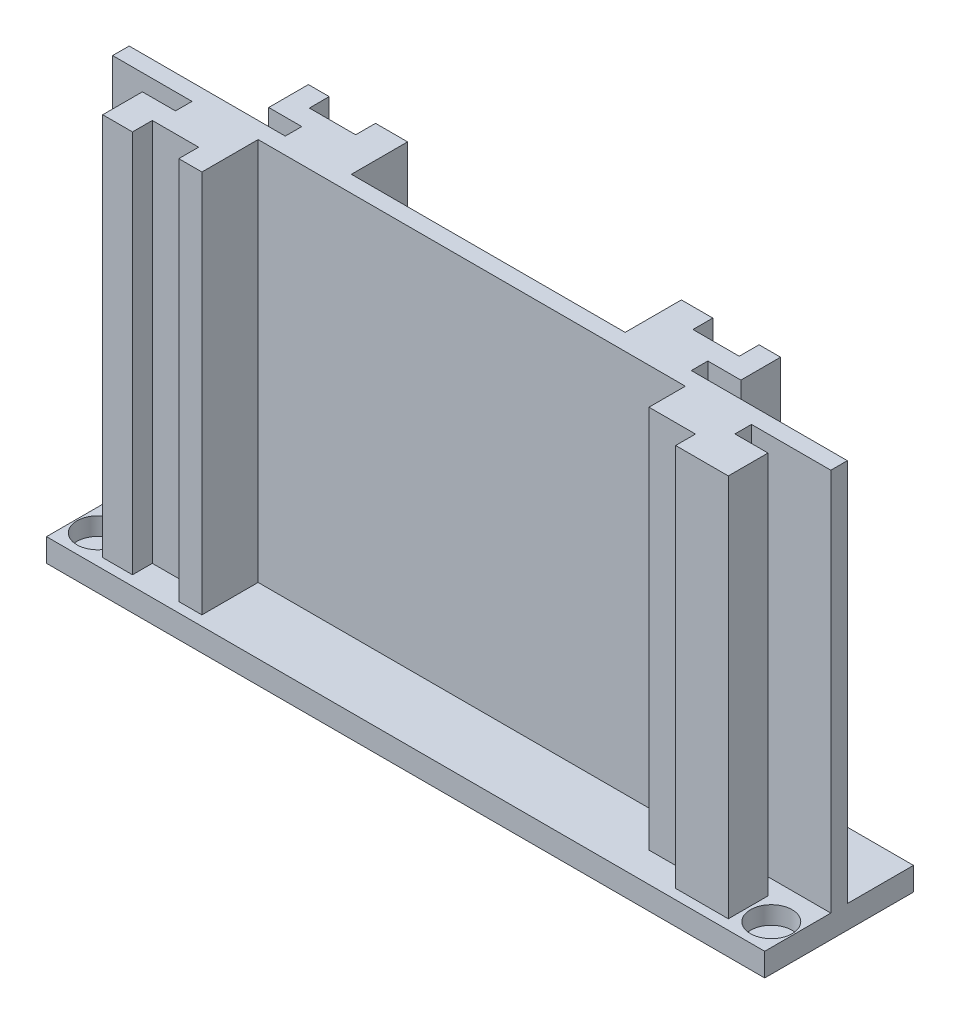
SolidWorks part; units mm, degrees
ref_plane "Front Plane" through (0, 0, 0) normal (0, 0, 1) x (1, 0, 0)
ref_plane "Top Plane" through (0, 0, 0) normal (0, 1, 0) x (1, 0, 0)
ref_plane "Right Plane" through (0, 0, 0) normal (1, 0, 0) x (0, 0, -1)
sketch "Sketch1" plane through (0, 0, 0) normal (0, 0, 1) x (1, 0, 0)
  line L1 (-54.3, -29) -> (54.3, -29)
  line L2 (-54.3, -29) -> (-54.3, 29)
  line L3 (-54.3, 29) -> (54.3, 29)
  line L4 (54.3, -29) -> (54.3, 29)
  line L5 (-54.3, -29) -> (54.3, 29) construction
  line L6 (-54.3, 29) -> (54.3, -29) construction
  point P0 (0, 0)
  dimension "D1" = 108.6
  dimension "D2" = 58
extrude "Boss-Extrude1" add sketch "Sketch1" along normal blind 2.5
sketch "Sketch2" plane through (0, 0, 2.5) normal (0, 0, 1) x (1, 0, 0)
  line L0 (54.3, 29) -> (-54.3, 29) construction
  line L1 (-42.3, 29) -> (-32.3, 29)
  line L2 (-42.3, 29) -> (-42.3, -29)
  line L3 (-42.3, -29) -> (-32.3, -29)
  line L4 (-32.3, 29) -> (-32.3, -29)
  line L5 (-54.3, -29) -> (54.3, -29) construction
  line L6 (0, 29) -> (0, -29) construction
  line L7 (32.3, 29) -> (42.3, 29)
  line L8 (32.3, 29) -> (32.3, -29)
  line L9 (32.3, -29) -> (42.3, -29)
  line L10 (42.3, 29) -> (42.3, -29)
  dimension "D1" = 84.6
  dimension "D2" = 10
extrude "Boss-Extrude2" add sketch "Sketch2" along normal blind 8.5
sketch "Sketch3" plane through (42.3, 0, 0) normal (1, 0, 0) x (0, 0, -1)
  line L0 (-11, -29) -> (-2.5, -29) construction
  line L1 (-11, 29) -> (-5, 29)
  line L2 (-11, 29) -> (-11, -29)
  line L3 (-11, -29) -> (-5, -29)
  line L4 (-5, 29) -> (-5, -29)
  dimension "D1" = 6
extrude "Boss-Extrude3" add sketch "Sketch3" along normal blind 5
sketch "Sketch4" plane through (-42.3, 0, 0) normal (-1, 0, 0) x (0, 0, 1)
  line L1 (11, 29) -> (5, 29)
  line L2 (11, 29) -> (11, -29)
  line L3 (11, -29) -> (5, -29)
  line L4 (5, 29) -> (5, -29)
  line L5 (11, -29) -> (2.5, -29) construction
  dimension "D1" = 6
extrude "Boss-Extrude4" add sketch "Sketch4" along normal blind 5
sketch "Sketch5" plane through (0, 0, 0) normal (0, 0, -1) x (-1, 0, 0)
  line L0 (-54.3, 29) -> (54.3, 29) construction
  line L1 (-30.7, 29) -> (-20.7, 29)
  line L2 (-30.7, 29) -> (-30.7, -29)
  line L3 (-30.7, -29) -> (-20.7, -29)
  line L4 (-20.7, 29) -> (-20.7, -29)
  line L5 (54.3, -29) -> (-54.3, -29) construction
  line L6 (0, 29) -> (0, -29) construction
  line L7 (20.7, 29) -> (30.7, 29)
  line L8 (20.7, 29) -> (20.7, -29)
  line L9 (20.7, -29) -> (30.7, -29)
  line L10 (30.7, 29) -> (30.7, -29)
  dimension "D1" = 61.4
  dimension "D2" = 10
extrude "Boss-Extrude5" add sketch "Sketch5" along normal blind 8.5
sketch "Sketch6" plane through (30.7, 0, 0) normal (1, 0, 0) x (0, 0, -1)
  line L0 (8.5, -29) -> (0, -29) construction
  line L1 (8.5, 29) -> (2.5, 29)
  line L2 (8.5, 29) -> (8.5, -29)
  line L3 (8.5, -29) -> (2.5, -29)
  line L4 (2.5, 29) -> (2.5, -29)
  dimension "D1" = 6
extrude "Boss-Extrude6" add sketch "Sketch6" along normal blind 5
sketch "Sketch7" plane through (-30.7, 0, 0) normal (-1, 0, 0) x (0, 0, 1)
  line L0 (-8.5, -29) -> (0, -29) construction
  line L1 (-8.5, 29) -> (-2.5, 29)
  line L2 (-8.5, 29) -> (-8.5, -29)
  line L3 (-8.5, -29) -> (-2.5, -29)
  line L4 (-2.5, 29) -> (-2.5, -29)
  dimension "D1" = 6
extrude "Boss-Extrude7" add sketch "Sketch7" along normal blind 5
sketch "Sketch8" plane through (0, -29, 0) normal (0, -1, 0) x (1, 0, 0)
  line L0 (-54.3, 1.25) -> (54.3, 1.25) construction
  line L1 (-54.3, 12.5) -> (54.3, 12.5)
  line L2 (-54.3, 12.5) -> (-54.3, -10)
  line L3 (-54.3, -10) -> (54.3, -10)
  line L4 (54.3, 12.5) -> (54.3, -10)
  line L5 (-54.3, 2.5) -> (-54.3, 0) construction
  line L6 (54.3, 2.5) -> (54.3, 0) construction
  point P10 (-54.3, 1.25)
  dimension "D1" = 22.5
extrude "Boss-Extrude8" add sketch "Sketch8" along normal blind 3.5
sketch "Sketch9" plane through (0, -29, 0) normal (0, 1, 0) x (1, 0, 0)
  line L0 (-54.3, -1.25) -> (54.3, -1.25) construction
  line L1 (-54.3, -2.5) -> (-54.3, 0) construction
  line L2 (54.3, -2.5) -> (54.3, 0) construction
  circle A0 centre (-39.45, 5.625) radius 3.15
  circle A1 centre (-50.925, -8.125) radius 3.15
  circle A2 centre (39.45, 5.625) radius 3.15
  circle A3 centre (50.925, -8.125) radius 3.15
extrude "Cut-Extrude1" cut sketch "Sketch9" against normal blind 2.7
sketch "Sketch10" plane through (0, 29, 0) normal (0, 1, 0) x (1, 0, 0)
  line L0 (-54.3, -1.25) -> (54.3, -1.25) construction
  line L1 (-54.3, -2.5) -> (-54.3, 0) construction
  line L2 (54.3, -2.5) -> (54.3, 0) construction
  line L3 (20.7, 8.5) -> (35.7, 8.5) construction
  line L4 (32.45, 8.5) -> (25.45, 8.5)
  line L5 (32.45, 8.5) -> (32.45, 5.5)
  line L6 (32.45, 5.5) -> (25.45, 5.5)
  line L7 (25.45, 8.5) -> (25.45, 5.5)
  line L8 (31.95, 11.25) -> (31.95, 16.25) construction
  line L9 (25.95, 16.25) -> (25.95, 11.25) construction
  line L10 (-35.7, 8.5) -> (-20.7, 8.5) construction
  line L11 (-32.55, 8.5) -> (-25.55, 8.5)
  line L12 (-32.55, 8.5) -> (-32.55, 5.5)
  line L13 (-32.55, 5.5) -> (-25.55, 5.5)
  line L14 (-25.55, 8.5) -> (-25.55, 5.5)
  line L15 (-32.05, 16.25) -> (-32.05, 11.25) construction
  line L16 (-26.05, 11.25) -> (-26.05, 16.25) construction
  line L17 (-32.3, -11) -> (-47.3, -11) construction
  line L18 (-42.8, -11) -> (-35.8, -11)
  line L19 (-42.8, -11) -> (-42.8, -8)
  line L20 (-42.8, -8) -> (-35.8, -8)
  line L21 (-35.8, -11) -> (-35.8, -8)
  line L22 (-36.8, -18.75) -> (-36.8, -13.75) construction
  line L23 (-41.8, -13.75) -> (-41.8, -18.75) construction
  line L24 (47.3, -11) -> (32.3, -11) construction
  line L25 (32.28, -11) -> (39.33, -11)
  line L26 (32.28, -11) -> (32.28, -8)
  line L27 (32.28, -8) -> (39.33, -8)
  line L28 (39.33, -11) -> (39.33, -8)
  line L29 (38.33, -18.75) -> (38.33, -13.75) construction
  line L30 (33.33, -13.75) -> (33.33, -18.75) construction
  dimension "D1" = 3
  dimension "D2" = 0.5
  dimension "D3" = 0.5
  dimension "D4" = 3
  dimension "D5" = 0.5
  dimension "D6" = 0.5
  dimension "D7" = 3
  dimension "D8" = 1
  dimension "D9" = 1
  dimension "D10" = 3
  dimension "D11" = 1
  dimension "D12" = 1.05
extrude "Cut-Extrude2" cut sketch "Sketch10" against normal up to surface (58 mm away) up to face at (50.925, -29, 11.275)
